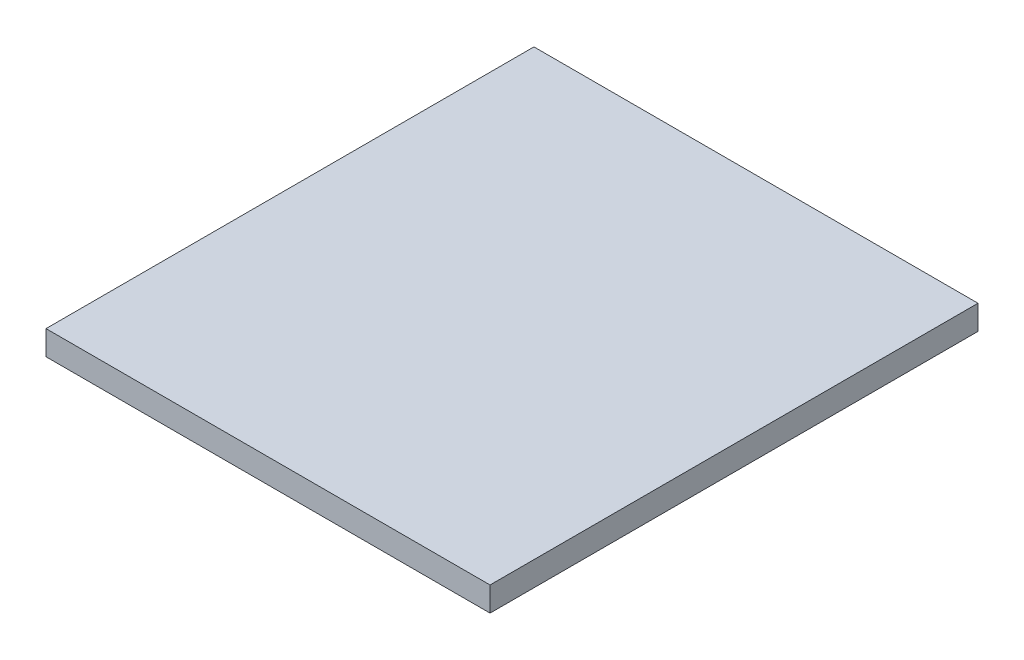
SolidWorks part; units mm, degrees
ref_plane "Alzado" through (0, 0, 0) normal (0, 0, 1) x (1, 0, 0)
ref_plane "Planta" through (0, 0, 0) normal (0, 1, 0) x (1, 0, 0)
ref_plane "Vista lateral" through (0, 0, 0) normal (1, 0, 0) x (0, 0, -1)
sketch "Croquis1" plane through (0, 0, 0) normal (0, 1, 0) x (1, 0, 0)
  line L1 (45.5, 50) -> (-45.5, 50)
  line L2 (45.5, 50) -> (45.5, -50)
  line L3 (45.5, -50) -> (-45.5, -50)
  line L4 (-45.5, 50) -> (-45.5, -50)
  line L5 (45.5, 50) -> (-45.5, -50) construction
  line L6 (45.5, -50) -> (-45.5, 50) construction
  point P0 (0, 0)
  dimension "D1" = 91
  dimension "D2" = 100
extrude "Saliente-Extruir1" add sketch "Croquis1" along normal blind 5
